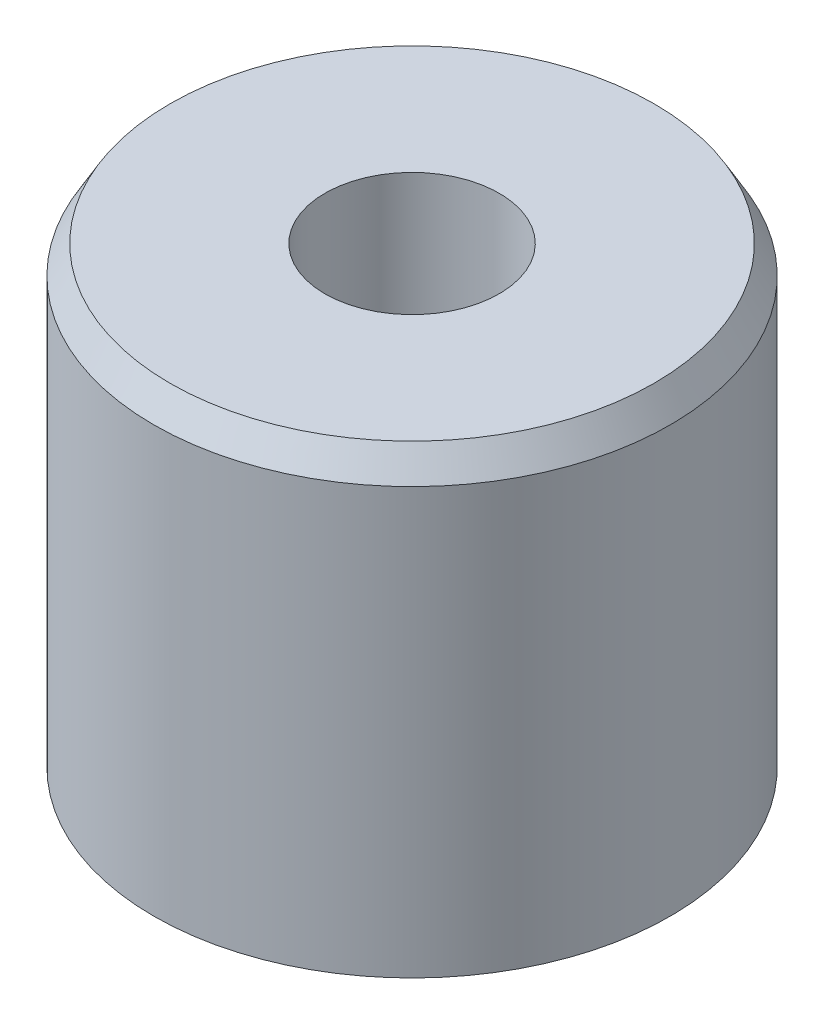
SolidWorks part; units mm, degrees
ref_plane "Front" through (0, 0, 0) normal (0, 0, 1) x (1, 0, 0)
ref_plane "Top" through (0, 0, 0) normal (0, 1, 0) x (1, 0, 0)
ref_plane "Right" through (0, 0, 0) normal (1, 0, 0) x (0, 0, -1)
sketch "Sketch1" plane through (0, 0, 0) normal (0, 1, 0) x (1, 0, 0)
  circle A0 centre (0, 0) radius 2.7
  circle A1 centre (0, 0) radius 8
  dimension "D1" = 5.4
  dimension "D2" = 16
extrude "Boss-Extrude1" add sketch "Sketch1" along normal blind 14.05
chamfer "Chamfer1" distance 3 angle 70 1 edges at (0, 0, 2.7)
chamfer "Chamfer2" distance 0.5 angle 60 1 edges at (0, 14.05, 8)
